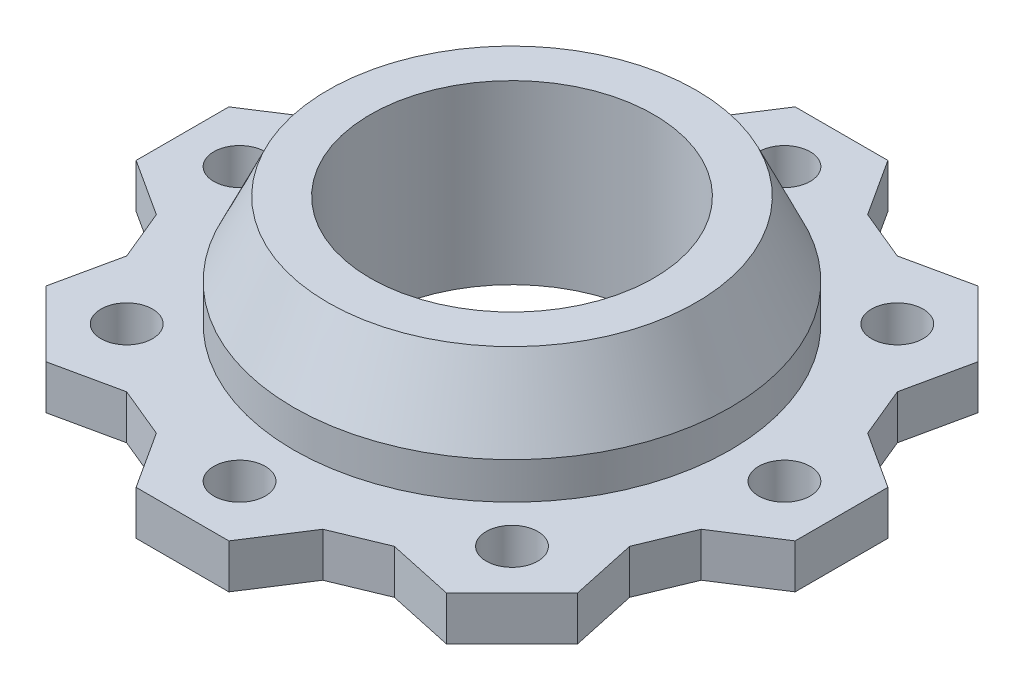
SolidWorks part; units mm, degrees
ref_plane "Front Plane" through (0, 0, 0) normal (0, 0, 1) x (1, 0, 0)
ref_plane "Top Plane" through (0, 0, 0) normal (0, 1, 0) x (1, 0, 0)
ref_plane "Right Plane" through (0, 0, 0) normal (1, 0, 0) x (0, 0, -1)
sketch "Sketch2" plane through (0, 0, 0) normal (0, 1, 0) x (1, 0, 0)
  line L0 (0, 58.6326) -> (0, -58.8328) construction
  line L1 (27.1883, 36.0978) -> (18.1726, 34.1533)
  line L2 (27.1883, 36.0978) -> (36.0978, 27.1883)
  line L3 (-6.3, 44.75) -> (6.3, 44.75)
  line L4 (-6.3, 44.75) -> (-11.3, 37)
  line L5 (6.3, 44.75) -> (11.3, 37)
  line L6 (36.0978, 27.1883) -> (34.1533, 18.1726)
  line L7 (44.75, 6.3) -> (37, 11.3)
  line L8 (44.75, 6.3) -> (44.75, -6.3)
  line L9 (44.75, -6.3) -> (37, -11.3)
  line L10 (36.0978, -27.1883) -> (34.1533, -18.1726)
  line L11 (36.0978, -27.1883) -> (27.1883, -36.0978)
  line L12 (27.1883, -36.0978) -> (18.1726, -34.1533)
  line L13 (6.3, -44.75) -> (11.3, -37)
  line L14 (6.3, -44.75) -> (-6.3, -44.75)
  line L15 (-6.3, -44.75) -> (-11.3, -37)
  line L16 (-27.1883, -36.0978) -> (-18.1726, -34.1533)
  line L17 (-27.1883, -36.0978) -> (-36.0978, -27.1883)
  line L18 (-36.0978, -27.1883) -> (-34.1533, -18.1726)
  line L19 (-44.75, -6.3) -> (-37, -11.3)
  line L20 (-44.75, -6.3) -> (-44.75, 6.3)
  line L21 (-44.75, 6.3) -> (-37, 11.3)
  line L22 (-36.0978, 27.1883) -> (-34.1533, 18.1726)
  line L23 (-36.0978, 27.1883) -> (-27.1883, 36.0978)
  line L24 (-27.1883, 36.0978) -> (-18.1726, 34.1533)
  line L25 (-34.1533, 18.1726) -> (-37, 11.3)
  line L26 (-18.1726, 34.1533) -> (-11.3, 37)
  line L27 (11.3, 37) -> (18.1726, 34.1533)
  line L28 (34.1533, 18.1726) -> (37, 11.3)
  line L29 (37, -11.3) -> (34.1533, -18.1726)
  line L30 (18.1726, -34.1533) -> (11.3, -37)
  line L31 (-11.3, -37) -> (-18.1726, -34.1533)
  line L32 (-34.1533, -18.1726) -> (-37, -11.3)
  circle A0 centre (0, 0) radius 37 construction
  circle A1 centre (0, 37) radius 3.5
  circle A2 centre (0, 0) radius 37 construction
  circle A3 centre (26.163, 26.163) radius 3.5
  circle A4 centre (0, 0) radius 37 construction
  circle A5 centre (37, 0) radius 3.5
  circle A6 centre (0, 0) radius 37 construction
  circle A7 centre (26.163, -26.163) radius 3.5
  circle A8 centre (0, 0) radius 37 construction
  circle A9 centre (0, -37) radius 3.5
  circle A10 centre (0, 0) radius 37 construction
  circle A11 centre (-26.163, -26.163) radius 3.5
  circle A12 centre (0, 0) radius 37 construction
  circle A13 centre (-37, 0) radius 3.5
  circle A14 centre (0, 0) radius 37 construction
  circle A15 centre (-26.163, 26.163) radius 3.5
  circle A16 centre (0, 0) radius 19.25
  point P63 (0, 0)
  dimension "D1" = 74
  dimension "D3" = 7
  dimension "D7" = 38.5
  dimension "D2" = 8
  dimension "D4" = 12.6
  dimension "D5" = 7.75
  dimension "D6" = 5
extrude "Boss-Extrude1" add sketch "Sketch2" along normal blind 6
sketch "Sketch3" plane through (0, 0, 0) normal (0, 0, 1) x (1, 0, 0)
  line L0 (0, 33.7582) -> (0, -30.6732) construction
  line L1 (-19.25, 21) -> (-25, 21)
  line L2 (-25, 21) -> (-29.6631, 11)
  line L3 (-29.6631, 11) -> (-29.6631, -3)
  line L4 (-29.6631, -3) -> (-19.25, -3)
  line L5 (-19.25, 21) -> (-19.25, -3)
  line L6 (-18.1726, 0) -> (-11.3, 0) construction
  line L7 (-27.1883, 6) -> (-18.1726, 6) construction
  line L8 (-18.1726, 6) -> (-11.3, 6) construction
  dimension "D1" = 3
  dimension "D2" = 10
  dimension "D3" = 5
  dimension "D4" = 65
  dimension "D5" = 25
  dimension "D6" = 19.25
revolve "Revolve1" add sketch "Sketch3" angle 360 about L0
